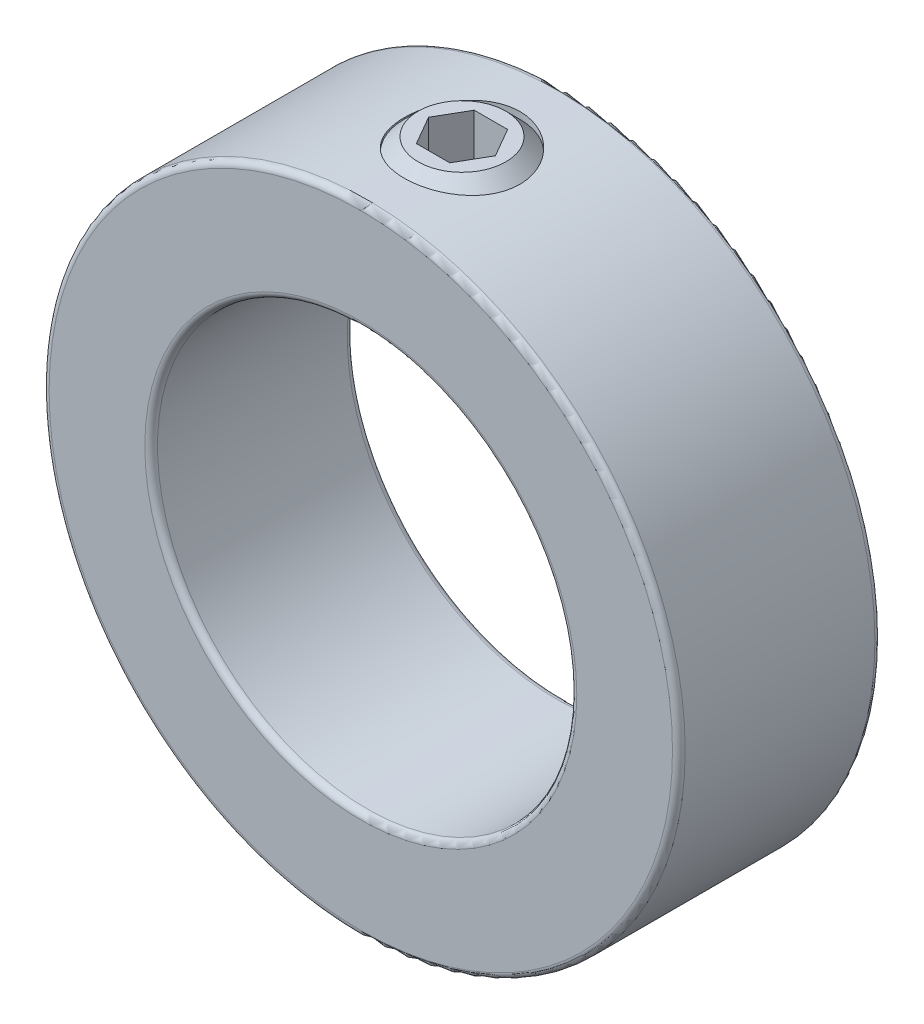
SolidWorks part; units mm, degrees
material "Plain Carbon Steel"
ref_plane "Front Plane" through (0, 0, 0) normal (0, 0, 1) x (1, 0, 0)
ref_plane "Top Plane" through (0, 0, 0) normal (0, 1, 0) x (1, 0, 0)
ref_plane "Right Plane" through (0, 0, 0) normal (1, 0, 0) x (0, 0, -1)
sketch "Sketch1" plane through (0, 0, 0) normal (0, 0, 1) x (1, 0, 0)
  circle A0 centre (0, 0) radius 34.925
  circle A1 centre (0, 0) radius 23.0188
  point P4 (34.925, 0)
  dimension "Bore Dia" = 46.0375
  dimension "OD" = 69.85
extrude "Extrude1" add sketch "Sketch1" along normal mid plane 22.225
sketch "Sketch2" plane through (41.275, 0, 0) normal (0, -1, 0) x (0, 0, -1)
  line L0 (11.1125, -41.275) -> (-11.1125, -41.275) construction
  line L1 (-11.1125, -6.35) -> (-11.1125, -76.2) construction
  line L2 (11.1125, -76.2) -> (11.1125, -6.35) construction
  circle A0 centre (0, -41.275) radius 6.35
  point P7 (0, -47.625)
  dimension "Set Screw Dia" = 12.7
extrude "Cut-Extrude1" cut sketch "Sketch2" against normal through all
fillet "Fillet1" radius 0.6985 4 edges at (23.0188, 0, -11.1125) (23.0188, 0, 11.1125) (34.925, 0, -11.1125) (34.925, 0, 11.1125)
sketch "Sketch3" plane through (0, 0, 0) normal (0, 0, 1) x (1, 0, 0)
  line L0 (-4.8164, 23.0188) -> (-1.8403, 23.0188)
  line L1 (0, 24.8591) -> (-1.8403, 23.0188)
  line L2 (0, 24.8591) -> (0, 35.7188)
  line L3 (0, 35.7188) -> (-4.8164, 35.7188)
  line L4 (-6.35, 24.5524) -> (-6.35, 34.1851)
  line L5 (0, 23.0188) -> (0, 0) construction
  line L6 (-6.35, 24.5524) -> (-6.35, 23.0188) construction
  line L7 (-6.35, 23.0188) -> (-4.8164, 23.0188) construction
  line L8 (-6.35, 34.1851) -> (-6.35, 35.7188) construction
  line L9 (-4.8164, 23.0188) -> (-6.35, 24.5524)
  line L10 (-6.35, 34.1851) -> (-4.8164, 35.7188)
  line L11 (-6.35, 35.7188) -> (-4.8164, 35.7188) construction
  line L12 (-1.8403, 23.0188) -> (0, 23.0188) construction
  line L13 (0, 23.0188) -> (0, 24.8591) construction
  circle A1 centre (0, 0) radius 23.0188 construction
  dimension "Screw Length" = 12.7
  dimension "D2" = 1.5336
  dimension "D1" = 1.8403
revolve "Revolve1" add sketch "Sketch3" angle 360 about L5
sketch "Sketch4" plane through (3.3734, 35.7187, 0) normal (0, -1, 0) x (0, 0, -1)
  line L1 (0, 0.2927) -> (-3.175, -1.5404)
  line L2 (-3.175, -1.5404) -> (-3.175, -5.2065)
  line L3 (-3.175, -5.2065) -> (0, -7.0396)
  line L4 (0, -7.0396) -> (3.175, -5.2065)
  line L5 (3.175, -5.2065) -> (3.175, -1.5404)
  line L6 (3.175, -1.5404) -> (0, 0.2927)
  circle A0 centre (0, -3.3734) radius 3.175 construction
  circle A1 centre (0, -3.3734) radius 3.6662 construction
  dimension "D1" = 7.3323
  dimension "Hex Size" = 6.35
extrude "Cut-Extrude2" cut sketch "Sketch4" along normal blind 6.35
equation "\"D1@Fillet1\" = \"OD@Sketch1\"*.01"
equation "\"D1@Cut-Extrude2\" = \"Hex Size@Sketch4\""
equation "\"D2@Sketch3\" =(\"Set Screw Dia@Sketch2\"-\"D1@Sketch4\")/3.5"
equation "\"D1@Sketch3\" = \"D2@Sketch3\"*1.2"
